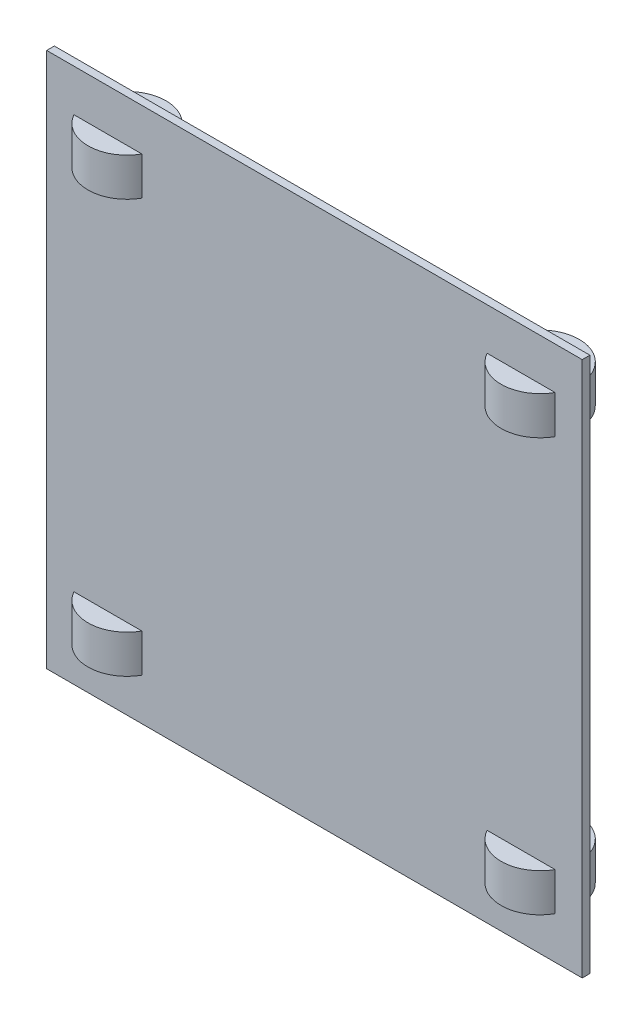
SolidWorks part; units mm, degrees
ref_plane "前视基准面" through (0, 0, 0) normal (0, 0, 1) x (1, 0, 0)
ref_plane "上视基准面" through (0, 0, 0) normal (0, 1, 0) x (1, 0, 0)
ref_plane "右视基准面" through (0, 0, 0) normal (1, 0, 0) x (0, 0, -1)
sketch "草图1" plane through (0, 0, 0) normal (0, 0, 1) x (1, 0, 0)
  line L1 (-350, -350) -> (350, -350)
  line L2 (-350, -350) -> (-350, 350)
  line L3 (-350, 350) -> (350, 350)
  line L4 (350, -350) -> (350, 350)
  line L5 (-350, -350) -> (350, 350) construction
  line L6 (-350, 350) -> (350, -350) construction
  point P0 (0, 0)
  dimension "D1" = 700
extrude "凸台-拉伸1" add sketch "草图1" along normal blind 10
ref_plane "基准面4" through (0, 270, 0) normal (0, 1, 0) x (1, 0, 0)
sketch "草图2" plane through (0, 270, 0) normal (0, 1, 0) x (1, 0, 0)
  line L0 (0, 0) -> (0, -102.8466) construction
  line L1 (-350, -10) -> (-350, 0) construction
  line L4 (350, -10) -> (-350, -10) construction
  circle A0 centre (-270, 15) radius 51
  circle A1 centre (270, 15) radius 51
  dimension "D2" = 102
  dimension "D1" = 80
  dimension "D3" = 25
extrude "凸台-拉伸2" add sketch "草图2" along normal mid plane 50
mirror "镜向1" about plane through (0, 0, 0) normal (0, 1, 0) of "凸台-拉伸2"
